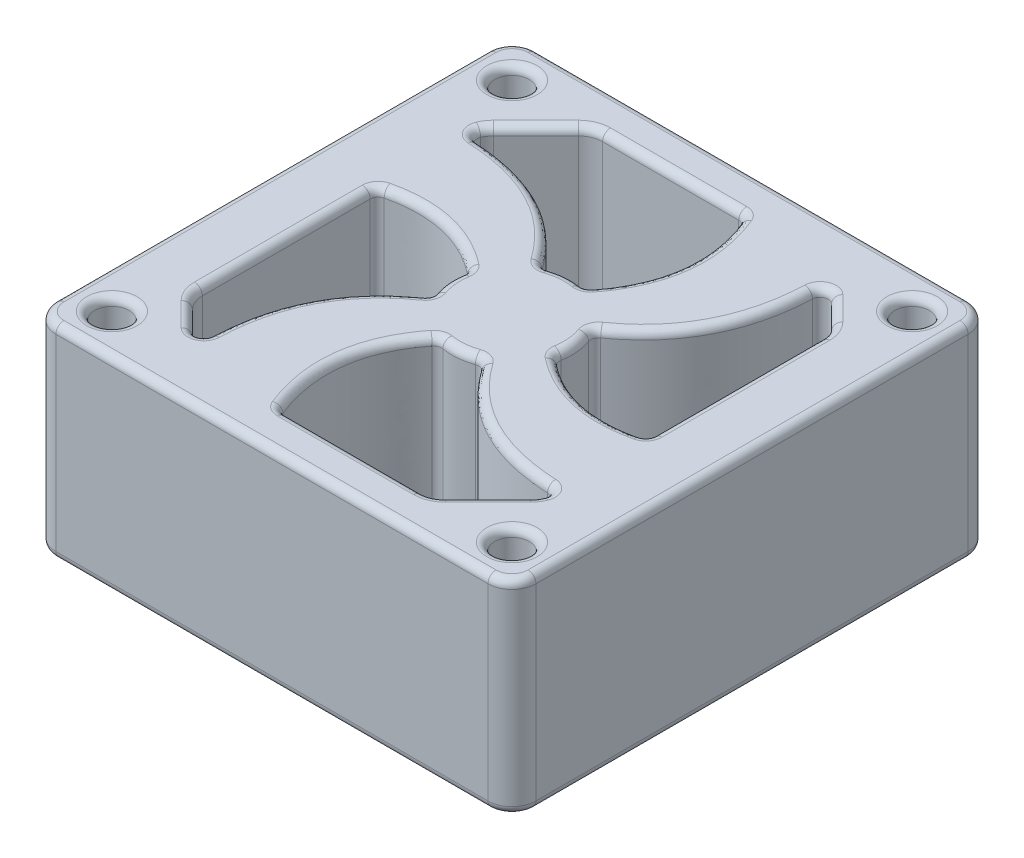
SolidWorks part; units mm, degrees
ref_plane "Front Plane" through (0, 0, 0) normal (0, 0, 1) x (1, 0, 0)
ref_plane "Top Plane" through (0, 0, 0) normal (0, 1, 0) x (1, 0, 0)
ref_plane "Right Plane" through (0, 0, 0) normal (1, 0, 0) x (0, 0, -1)
sketch "Sketch1" plane through (0, 0, 0) normal (0, 1, 0) x (1, 0, 0)
  line L0 (0, 0) -> (8.0136, 0) construction
  line L1 (-27, 30) -> (27, 30)
  line L2 (-30, 27) -> (-30, -27)
  line L3 (-27, -30) -> (27, -30)
  line L4 (30, 27) -> (30, -27)
  line L5 (-30, 30) -> (30, -30) construction
  line L6 (-30, -30) -> (30, 30) construction
  line L7 (-13.6863, 25) -> (13.6863, 25) construction
  line L8 (16.4712, 23.4578) -> (21.1213, 18.8076)
  line L9 (0, 0) -> (0, 28.2474) construction
  line L10 (22, 16.6863) -> (22, -5.0587)
  line L11 (-22, 16.6863) -> (-22, 16.4876)
  line L12 (-15.8076, 24.1213) -> (-21.1213, 18.8076)
  line L13 (15.8076, -24.1213) -> (21.1213, -18.8076)
  line L14 (-4, -25) -> (13.6863, -25)
  line L15 (-16.4712, -23.4578) -> (-21.1213, -18.8076)
  line L16 (-13.6863, 25) -> (4, 25)
  line L17 (-22, 5.0587) -> (-22, -16.6863)
  line L18 (22, -16.4876) -> (22, -16.6863)
  circle A0 centre (-25, 25) radius 2.15
  circle A1 centre (25, 25) radius 2.15
  circle A2 centre (25, -25) radius 2.15
  circle A3 centre (-25, -25) radius 2.15
  arc A4 (-30, -27) -> (-27, -30) centre (-27, -27) ccw
  arc A5 (27, -30) -> (30, -27) centre (27, -27) ccw
  arc A6 (27, 30) -> (30, 27) centre (27, 27) cw
  arc A7 (-27, 30) -> (-30, 27) centre (-27, 27) ccw
  arc A8 (1.8158, 7.2769) -> (-3.2062, 6.7801) centre (0, 0) ccw
  arc A10 (21.1213, 18.8076) -> (22, 16.6863) centre (19, 16.6863) cw
  arc A11 (21.1213, -18.8076) -> (22, -16.6863) centre (19, -16.6863) ccw
  arc A12 (15.8076, -24.1213) -> (13.6863, -25) centre (13.6863, -22) cw
  arc A14 (-21.1213, -18.8076) -> (-22, -16.6863) centre (-19, -16.6863) cw
  arc A15 (-22, 16.6863) -> (-21.1213, 18.8076) centre (-19, 16.6863) cw
  arc A16 (-15.8076, 24.1213) -> (-13.6863, 25) centre (-13.6863, 22) cw
  arc A17 (-1.8158, -7.2769) -> (3.2062, -6.7801) centre (0, 0) ccw
  arc A18 (7.2769, -1.8158) -> (6.7801, 3.2062) centre (0, 0) ccw
  arc A19 (-7.2769, 1.8158) -> (-6.7801, -3.2062) centre (0, 0) ccw
  spline S0 degree 2 poles (1.8158, 7.2769) (8.285, 15.015) (4, 25) knots 0 0 0 1 1 1
  spline S1 degree 2 poles (6.7801, 3.2062) (16.9101, 9.8905) (16.4712, 23.4578) knots 0 0 0 1 1 1
  spline S2 degree 3 poles (7.2769, -1.8158) (11.6471, -5.4694) (16.5548, -6.5503) (22, -5.0587) knots 0 0 0 0 0.847145 0.847145 0.847145 0.847145
  spline S3 degree 3 poles (3.2062, -6.7801) (7.4196, -13.1656) (13.6843, -16.4014) (22, -16.4876) knots 0 0 0 0 0.945524 0.945524 0.945524 0.945524
  spline S4 degree 2 poles (-1.8158, -7.2769) (-8.285, -15.015) (-4, -25) knots 0 0 0 1 1 1
  spline S5 degree 2 poles (-6.7801, -3.2062) (-16.9101, -9.8905) (-16.4712, -23.4578) knots 0 0 0 1 1 1
  spline S6 degree 3 poles (-7.2769, 1.8158) (-11.6471, 5.4694) (-16.5548, 6.5503) (-22, 5.0587) knots 0 0 0 0 0.847145 0.847145 0.847145 0.847145
  spline S7 degree 3 poles (-3.2062, 6.7801) (-7.4196, 13.1656) (-13.6843, 16.4014) (-22, 16.4876) knots 0 0 0 0 0.945524 0.945524 0.945524 0.945524
  point P0 (0, 0)
  point P39 (0, 25)
  point P40 (22, 0)
  point P43 (-22, 0)
  point P45 (14.9289, 25)
  point P48 (22, 17.9289)
  point P51 (22, -17.9289)
  point P54 (14.9289, -25)
  point P57 (-14.9289, -25)
  point P60 (-22, -17.9289)
  point P63 (-22, 17.9289)
  point P66 (-14.9289, 25)
  point P91 (0, 0)
  dimension "D3" = 4.3
  dimension "D4" = 4.3
  dimension "D5" = 50
  dimension "D6" = 3
  dimension "D7" = 15
  dimension "D11" = 4
  dimension "D1" = 60
  dimension "D2" = 60
  dimension "D8" = 8
  dimension "D9" = 10
  dimension "D10" = 45
extrude "Boss-Extrude1" add sketch "Sketch1" along normal blind 25.5
fillet "Fillet1" radius 1 2 edges at (-25, 25.5, 22.85) (-3.2062, 12.75, -6.7801)
fillet "Fillet2" radius 1 3 edges at (-22, 12.75, -16.4876) (1.8158, 12.75, -7.2769) (4, 12.75, -25)
fillet "Fillet3" radius 1 23 edges at (-21.6905, 25.5, -16.9203) (-0.6445, 25.5, -7.4723) (-5.1774, 25.5, -25) (-14.8343, 25.5, -24.7716) (-18.4645, 25.5, -21.4645) (-21.4925, 25.5, -18.3559) (3.8929, 0, -24.8276) (1.7831, 0, -7.4471) (-3.1399, 0, -7.0596) (3.8929, 25.5, -24.8276) (1.7831, 25.5, -7.4471) (-3.1399, 25.5, -7.0596) (3.2062, 12.75, 6.7801) (-21.6905, 0, -16.9203) (-21.4925, 0, -18.3559) (-18.4645, 0, -21.4645) (-14.8343, 0, -24.7716) (-5.1774, 0, -25) (-0.6445, 0, -7.4723)
fillet "Fillet4" radius 1 3 edges at (22, 12.75, 16.4876) (-1.8158, 12.75, 7.2769) (-4, 12.75, 25)
fillet "Fillet5" radius 1 77 edges at (21.6905, 25.5, 16.9203) (0.6445, 25.5, 7.4723) (5.1774, 25.5, 25) (14.8343, 25.5, 24.7716) (18.4645, 25.5, 21.4645) (21.4925, 25.5, 18.3559) (-3.8929, 0, 24.8276) (-1.7831, 0, 7.4471) (3.1399, 0, 7.0596) (-3.8929, 25.5, 24.8276) (-1.7831, 25.5, 7.4471) (3.1399, 25.5, 7.0596) (-25, 0, 22.85) (25, 25.5, 22.85) (25, 0, 22.85) (25, 25.5, -22.85) (25, 0, -22.85) (-25, 25.5, -22.85) (-25, 0, -22.85) (-29.1213, 25.5, 29.1213) (-30, 25.5, 0) (-29.1213, 25.5, -29.1213) (0, 25.5, -30) (29.1213, 25.5, -29.1213) (30, 25.5, 0) (29.1213, 25.5, 29.1213) (0, 25.5, 30) (29.1213, 0, 29.1213) (30, 0, 0) (29.1213, 0, -29.1213) (0, 0, -30) (-29.1213, 0, -29.1213) (-30, 0, 0) (-29.1213, 0, 29.1213) (0, 0, 30) (22, 12.75, 5.0587) (7.2769, 12.75, 1.8158) (7.4636, 25.5, -0.7382) (22, 25.5, -5.8138) (21.7716, 25.5, -17.8343) (18.7963, 25.5, -21.1327) (16.4712, 12.75, -23.4578) (18.7963, 0, -21.1327) (21.7716, 0, -17.8343) (22, 0, -5.8138) (7.4636, 0, -0.7382) (6.7801, 12.75, -3.2062) (-7.2769, 12.75, -1.8158) (-22, 12.75, -5.0587) (-22, 25.5, 5.8138) (-21.7716, 25.5, 17.8343) (-18.7963, 25.5, 21.1327) (-16.4712, 12.75, 23.4578) (-18.7963, 0, 21.1327) (-21.7716, 0, 17.8343) (-22, 0, 5.8138) (-7.4636, 0, 0.7382) (-6.7801, 12.75, 3.2062) (-7.4636, 25.5, 0.7382) (21.6905, 0, 16.9203) (21.4925, 0, 18.3559) (18.4645, 0, 21.4645) (14.8343, 0, 24.7716) (5.1774, 0, 25) (0.6445, 0, 7.4723)
